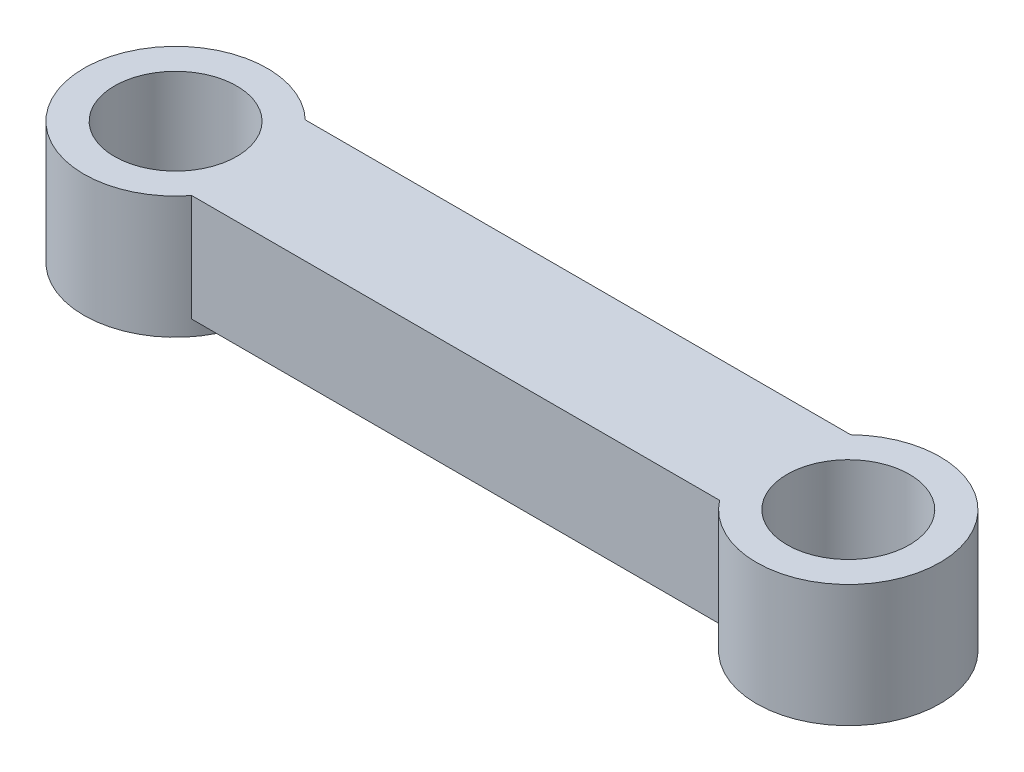
SolidWorks part; units mm, degrees
ref_plane "Plan de face" through (0, 0, 0) normal (0, 0, 1) x (1, 0, 0)
ref_plane "Plan de dessus" through (0, 0, 0) normal (0, 1, 0) x (1, 0, 0)
ref_plane "Plan de droite" through (0, 0, 0) normal (1, 0, 0) x (0, 0, -1)
sketch "Esquisse1" plane through (0, 0, 0) normal (0, 1, 0) x (1, 0, 0)
  line L1 (0, 0) -> (28, 0)
  line L2 (0, 0) -> (0, 4)
  line L3 (0, 4) -> (28, 4)
  line L4 (28, 0) -> (28, 4)
  dimension "D1" = 28
  dimension "D2" = 4
extrude "Boss.-Extru.1" add sketch "Esquisse1" along normal blind 3.5
sketch "Esquisse2" plane through (0, 3.5, 0) normal (0, 1, 0) x (1, 0, 0)
  line L0 (0, 4) -> (0, 0) construction
  line L1 (28, 0) -> (28, 4) construction
  circle A0 centre (3, 1.8407) radius 3
  circle A1 centre (25, 1.8407) radius 3
  dimension "D1" = 6
  dimension "D3" = 6
  dimension "D2" = 3
  dimension "D4" = 3
extrude "Boss.-Extru.2" add sketch "Esquisse2" against normal blind 4
sketch "Esquisse3" plane through (0, 3.5, 0) normal (0, 1, 0) x (1, 0, 0)
  circle A0 centre (3, 1.8407) radius 2
  circle A1 centre (25, 1.8407) radius 2
  arc A2 (22.6311, 0) -> (27.3689, 0) centre (25, 1.8407) ccw construction
  arc A3 (0.6311, 0) -> (5.3689, 0) centre (3, 1.8407) ccw construction
  dimension "D1" = 4
  dimension "D2" = 4
  dimension "D3" = 0
  dimension "D4" = 0
extrude "Enlèv. mat.-Extru.1" cut sketch "Esquisse3" against normal blind 4
sketch "Esquisse4" plane through (0, 3.5, 0) normal (0, 1, 0) x (1, 0, 0)
  line L0 (0.9174, 4) -> (-0.492, 5.4612)
  line L1 (-0.492, 5.4612) -> (-4.2459, 1.8407)
  line L2 (-4.2459, 1.8407) -> (-0.7302, -1.8045)
  line L3 (-0.7302, -1.8045) -> (0.6311, 0)
  arc A0 (0.6311, 0) -> (0.9174, 4) centre (3, 1.8407) cw
  arc A1 (5.0826, 4) -> (0.9174, 4) centre (3, 1.8407) ccw construction
extrude "Enlèv. mat.-Extru.2" cut sketch "Esquisse4" against normal blind 4
sketch "Esquisse5" plane through (0, 3.5, 0) normal (0, 1, 0) x (1, 0, 0)
  line L0 (28, 4) -> (27.0826, 4) construction
  line L1 (27.0826, 4) -> (30.6327, 7.5501)
  line L2 (30.6327, 7.5501) -> (35.5972, 2.5856)
  line L3 (35.5972, 2.5856) -> (29.6075, -3.404)
  line L4 (29.6075, -3.404) -> (27.3689, 0)
  arc A0 (27.3689, 0) -> (27.0826, 4) centre (25, 1.8407) ccw
extrude "Enlèv. mat.-Extru.3" cut sketch "Esquisse5" against normal blind 4
